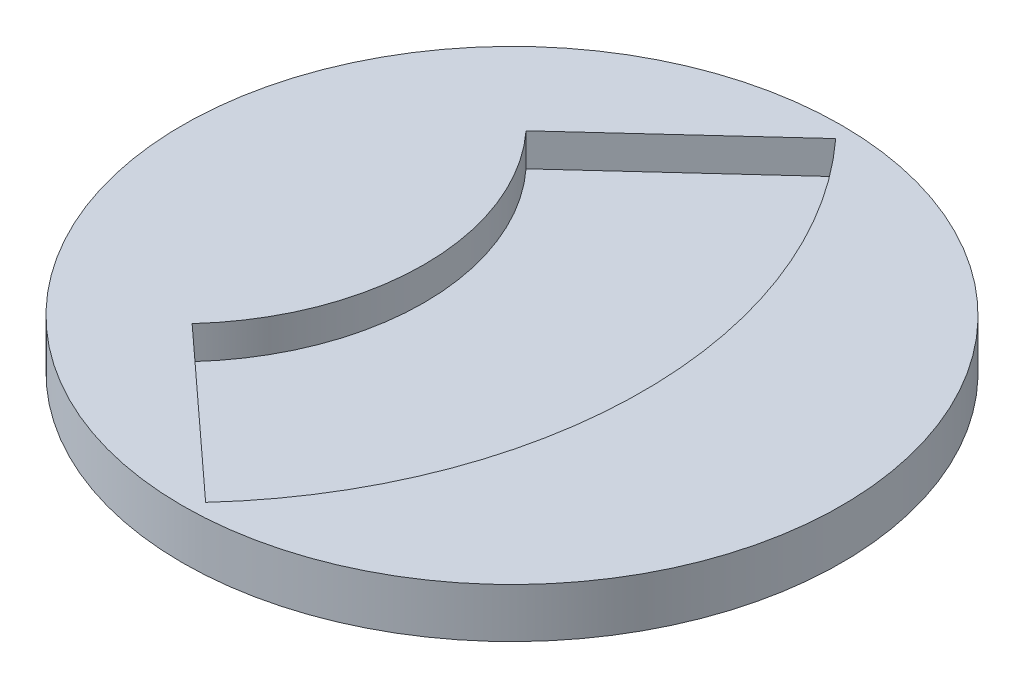
SolidWorks part; units mm, degrees
ref_plane "Front Plane" through (0, 0, 0) normal (0, 0, 1) x (1, 0, 0)
ref_plane "Top Plane" through (0, 0, 0) normal (0, 1, 0) x (1, 0, 0)
ref_plane "Right Plane" through (0, 0, 0) normal (1, 0, 0) x (0, 0, -1)
sketch "Sketch1" plane through (0, 0, 0) normal (0, 0, 1) x (1, 0, 0)
  line L0 (0.9, -2) -> (0.9, 2)
  line L1 (0.9, 2) -> (0, 2)
  line L2 (0, 2) -> (0, 5)
  line L3 (0, 5) -> (20, 5)
  line L4 (20, 5) -> (20, 2)
  line L5 (20, 2) -> (2.9, 2)
  line L6 (2.9, 2) -> (2.9, -2)
  line L7 (2.9, -2) -> (0.9, -2)
  line L8 (0, -3.5392) -> (0, 6.3608) construction
  point P9 (0.9, 0)
  point P11 (0.9, -2.1919)
  dimension "D1" = 1.8
  dimension "D2" = 2
  dimension "D3" = 3
  dimension "D4" = 4
  dimension "D5" = 40
revolve "Revolve1" add sketch "Sketch1" angle 360 about L8
sketch "Sketch2" plane through (0, 5, 0) normal (0, 1, 0) x (1, 0, 0)
  line L0 (0.5263, 19.1192) -> (-9.2795, 10.1339)
  line L1 (0.5263, -19.1192) -> (-9.2795, -10.1339)
  line L2 (7.9613, 0) -> (-5.3387, 0) construction
  arc A0 (0.5263, 19.1192) -> (0.5263, -19.1192) centre (-20.3387, 0) cw
  arc A1 (-9.2795, 10.1339) -> (-9.2795, -10.1339) centre (-20.3387, 0) cw
  dimension "IR" = 15
  dimension "OR" = 28.3
  dimension "D1" = 20.3387
extrude "Cut-Extrude1" cut sketch "Sketch2" against normal blind 2
equation "\"D1@Sketch2\"=2*(\"OR@Sketch2\"^3-\"IR@Sketch2\"^3)*sin(\"a@Sketch2\")/(3*\"a@Sketch2\"*(\"OR@Sketch2\"^2-\"IR@Sketch2\"^2))"
